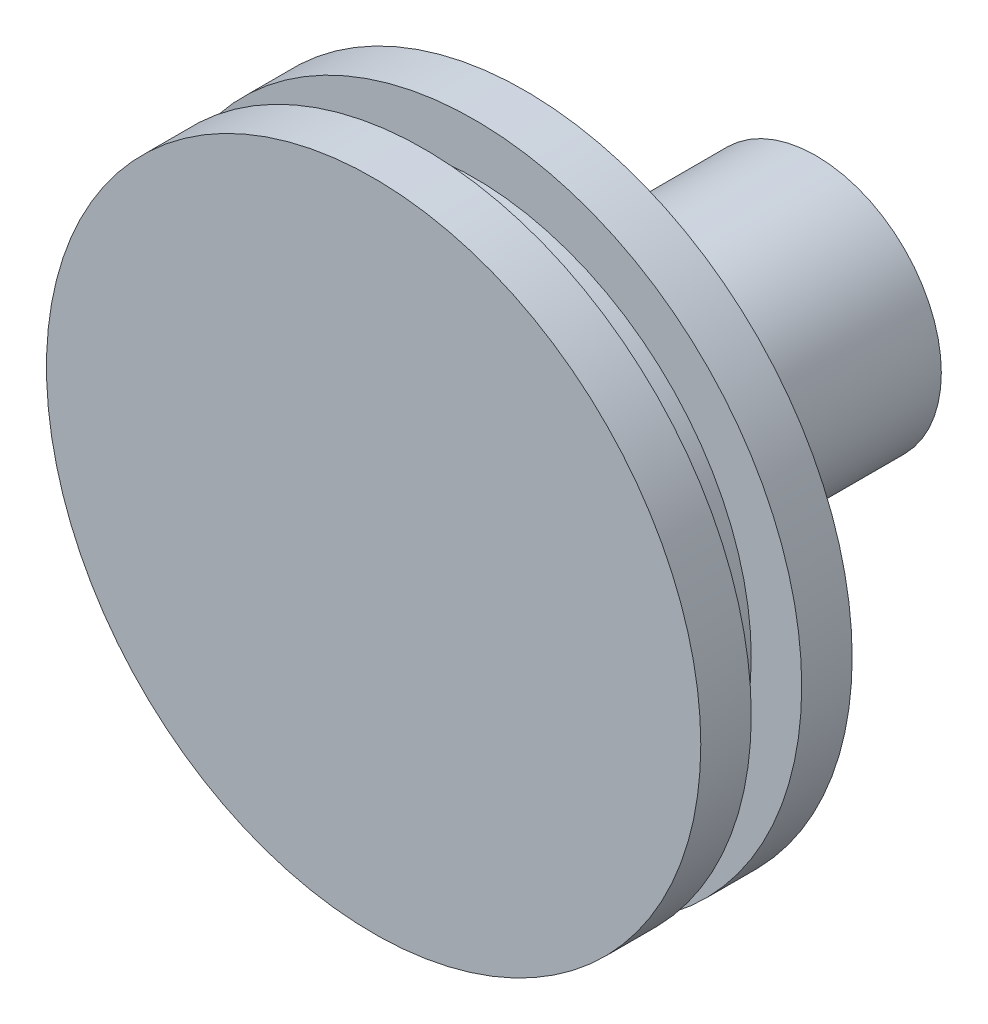
SolidWorks part; units mm, degrees
ref_plane "Front Plane" through (0, 0, 0) normal (0, 0, 1) x (1, 0, 0)
ref_plane "Top Plane" through (0, 0, 0) normal (0, 1, 0) x (1, 0, 0)
ref_plane "Right Plane" through (0, 0, 0) normal (1, 0, 0) x (0, 0, -1)
sketch "Sketch1" plane through (0, 0, 0) normal (0, 0, 1) x (1, 0, 0)
  line L2 (-1.8868, -1.825) -> (1.8868, -1.825)
  line L3 (1.8868, 1.825) -> (-1.8868, 1.825)
  line L4 (-1.8868, -1.825) -> (1.8868, -1.825)
  line L5 (1.8868, 1.825) -> (-1.8868, 1.825)
  circle A0 centre (0, 0) radius 3.725 construction
  circle A1 centre (0, 0) radius 3.725
  arc A2 (1.8868, -1.825) -> (1.8868, 1.825) centre (0, 0) ccw
  arc A3 (-1.8868, 1.825) -> (-1.8868, -1.825) centre (0, 0) ccw
  arc A4 (1.8868, -1.825) -> (1.8868, 1.825) centre (0, 0) ccw
  arc A5 (-1.8868, 1.825) -> (-1.8868, -1.825) centre (0, 0) ccw
  dimension "D1" = 0
extrude "Boss-Extrude1" add sketch "Sketch1" along normal up to surface (8.65 mm away)
sketch "Sketch2" plane through (0, 0, 8.65) normal (0, 0, 1) x (1, 0, 0)
  circle A0 centre (0, 0) radius 9.725
  circle A1 centre (0, 0) radius 3.725 construction
  dimension "D1" = 6
extrude "Boss-Extrude2" add sketch "Sketch2" along normal blind 1.5
sketch "Sketch3" plane through (0, 0, 10.15) normal (0, 0, 1) x (1, 0, 0)
  circle A0 centre (0, 0) radius 8.225
  circle A2 centre (0, 0) radius 9.725 construction
  dimension "D1" = 1.5
extrude "Boss-Extrude3" add sketch "Sketch3" along normal blind 1.5
sketch "Sketch5" plane through (0, 0, 11.65) normal (0, 0, 1) x (1, 0, 0)
  circle A0 centre (0, 0) radius 9.725 construction
  circle A1 centre (0, 0) radius 9.725
extrude "Boss-Extrude5" add sketch "Sketch5" along normal blind 1.5
